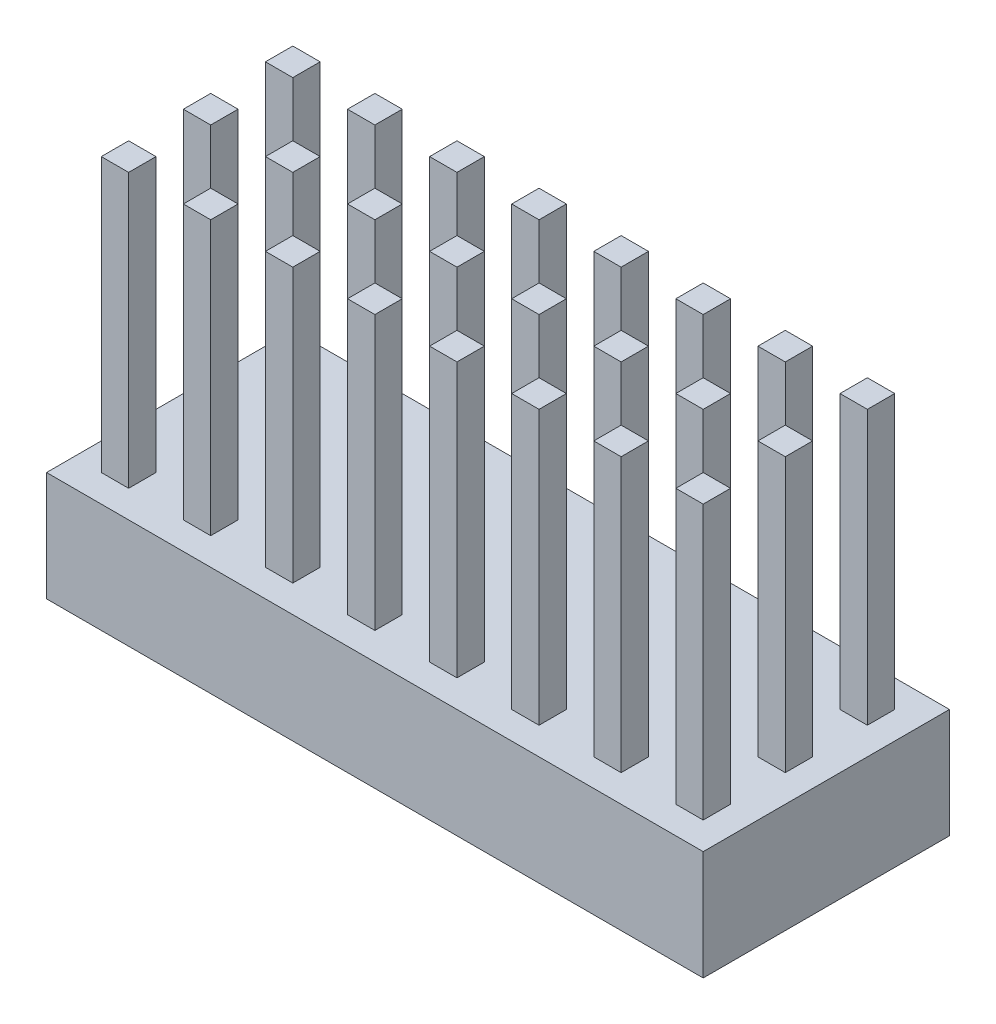
SolidWorks part; units mm, degrees
ref_plane "Front Plane" through (0, 0, 0) normal (0, 0, 1) x (1, 0, 0)
ref_plane "Top Plane" through (0, 0, 0) normal (0, 1, 0) x (1, 0, 0)
ref_plane "Right Plane" through (0, 0, 0) normal (1, 0, 0) x (0, 0, -1)
sketch "Sketch1" plane through (0, 0, 0) normal (0, 1, 0) x (1, 0, 0)
  line L1 (0, 0) -> (18.288, 0)
  line L2 (0, 0) -> (0, 6.858)
  line L3 (0, 6.858) -> (18.288, 6.858)
  line L4 (18.288, 0) -> (18.288, 6.858)
  dimension "D1" = 18.288
  dimension "D2" = 6.858
extrude "Extrude1" add sketch "Sketch1" along normal blind 3.048
sketch "Sketch2" plane through (0, 3.048, 0) normal (0, 1, 0) x (1, 0, 0)
  line L0 (0, 6.858) -> (0, 0) construction
  line L1 (3.048, 5.334) -> (3.81, 5.334)
  line L2 (3.048, 5.334) -> (3.048, 6.096)
  line L3 (3.048, 6.096) -> (3.81, 6.096)
  line L4 (3.81, 5.334) -> (3.81, 6.096)
  line L5 (0.762, 5.334) -> (1.524, 5.334)
  line L6 (0.762, 5.334) -> (0.762, 6.096)
  line L7 (0.762, 6.096) -> (1.524, 6.096)
  line L8 (1.524, 5.334) -> (1.524, 6.096)
  line L10 (18.288, 6.858) -> (0, 6.858) construction
  line L11 (5.334, 5.334) -> (6.096, 5.334)
  line L12 (5.334, 5.334) -> (5.334, 6.096)
  line L13 (5.334, 6.096) -> (6.096, 6.096)
  line L14 (6.096, 5.334) -> (6.096, 6.096)
  line L15 (7.62, 5.334) -> (8.382, 5.334)
  line L16 (7.62, 5.334) -> (7.62, 6.096)
  line L17 (7.62, 6.096) -> (8.382, 6.096)
  line L18 (8.382, 5.334) -> (8.382, 6.096)
  line L19 (9.906, 5.334) -> (10.668, 5.334)
  line L20 (9.906, 5.334) -> (9.906, 6.096)
  line L21 (9.906, 6.096) -> (10.668, 6.096)
  line L22 (10.668, 5.334) -> (10.668, 6.096)
  line L23 (12.192, 5.334) -> (12.954, 5.334)
  line L24 (12.192, 5.334) -> (12.192, 6.096)
  line L25 (12.192, 6.096) -> (12.954, 6.096)
  line L26 (12.954, 5.334) -> (12.954, 6.096)
  line L27 (14.478, 5.334) -> (15.24, 5.334)
  line L28 (14.478, 5.334) -> (14.478, 6.096)
  line L29 (14.478, 6.096) -> (15.24, 6.096)
  line L30 (15.24, 5.334) -> (15.24, 6.096)
  line L31 (16.764, 5.334) -> (17.526, 5.334)
  line L32 (16.764, 5.334) -> (16.764, 6.096)
  line L33 (16.764, 6.096) -> (17.526, 6.096)
  line L34 (17.526, 5.334) -> (17.526, 6.096)
  line L35 (0.762, 3.048) -> (1.524, 3.048)
  line L36 (0.762, 3.048) -> (0.762, 3.81)
  line L37 (0.762, 3.81) -> (1.524, 3.81)
  line L38 (1.524, 3.048) -> (1.524, 3.81)
  line L39 (3.048, 3.048) -> (3.81, 3.048)
  line L40 (3.048, 3.048) -> (3.048, 3.81)
  line L41 (3.048, 3.81) -> (3.81, 3.81)
  line L42 (3.81, 3.048) -> (3.81, 3.81)
  line L43 (5.334, 3.048) -> (6.096, 3.048)
  line L44 (5.334, 3.048) -> (5.334, 3.81)
  line L45 (5.334, 3.81) -> (6.096, 3.81)
  line L46 (6.096, 3.048) -> (6.096, 3.81)
  line L47 (7.62, 3.048) -> (8.382, 3.048)
  line L48 (7.62, 3.048) -> (7.62, 3.81)
  line L49 (7.62, 3.81) -> (8.382, 3.81)
  line L50 (8.382, 3.048) -> (8.382, 3.81)
  line L51 (9.906, 3.048) -> (10.668, 3.048)
  line L52 (9.906, 3.048) -> (9.906, 3.81)
  line L53 (9.906, 3.81) -> (10.668, 3.81)
  line L54 (10.668, 3.048) -> (10.668, 3.81)
  line L55 (12.192, 3.048) -> (12.954, 3.048)
  line L56 (12.192, 3.048) -> (12.192, 3.81)
  line L57 (12.192, 3.81) -> (12.954, 3.81)
  line L58 (12.954, 3.048) -> (12.954, 3.81)
  line L59 (14.478, 3.048) -> (15.24, 3.048)
  line L60 (14.478, 3.048) -> (14.478, 3.81)
  line L61 (14.478, 3.81) -> (15.24, 3.81)
  line L62 (15.24, 3.048) -> (15.24, 3.81)
  line L63 (16.764, 3.048) -> (17.526, 3.048)
  line L64 (16.764, 3.048) -> (16.764, 3.81)
  line L65 (16.764, 3.81) -> (17.526, 3.81)
  line L66 (17.526, 3.048) -> (17.526, 3.81)
  line L67 (0.762, 0.762) -> (1.524, 0.762)
  line L68 (0.762, 0.762) -> (0.762, 1.524)
  line L69 (0.762, 1.524) -> (1.524, 1.524)
  line L70 (1.524, 0.762) -> (1.524, 1.524)
  line L71 (3.048, 0.762) -> (3.81, 0.762)
  line L72 (3.048, 0.762) -> (3.048, 1.524)
  line L73 (3.048, 1.524) -> (3.81, 1.524)
  line L74 (3.81, 0.762) -> (3.81, 1.524)
  line L75 (5.334, 0.762) -> (6.096, 0.762)
  line L76 (5.334, 0.762) -> (5.334, 1.524)
  line L77 (5.334, 1.524) -> (6.096, 1.524)
  line L78 (6.096, 0.762) -> (6.096, 1.524)
  line L79 (7.62, 0.762) -> (8.382, 0.762)
  line L80 (7.62, 0.762) -> (7.62, 1.524)
  line L81 (7.62, 1.524) -> (8.382, 1.524)
  line L82 (8.382, 0.762) -> (8.382, 1.524)
  line L83 (9.906, 0.762) -> (10.668, 0.762)
  line L84 (9.906, 0.762) -> (9.906, 1.524)
  line L85 (9.906, 1.524) -> (10.668, 1.524)
  line L86 (10.668, 0.762) -> (10.668, 1.524)
  line L87 (12.192, 0.762) -> (12.954, 0.762)
  line L88 (12.192, 0.762) -> (12.192, 1.524)
  line L89 (12.192, 1.524) -> (12.954, 1.524)
  line L90 (12.954, 0.762) -> (12.954, 1.524)
  line L91 (14.478, 0.762) -> (15.24, 0.762)
  line L92 (14.478, 0.762) -> (14.478, 1.524)
  line L93 (14.478, 1.524) -> (15.24, 1.524)
  line L94 (15.24, 0.762) -> (15.24, 1.524)
  line L95 (16.764, 0.762) -> (17.526, 0.762)
  line L96 (16.764, 0.762) -> (16.764, 1.524)
  line L97 (16.764, 1.524) -> (17.526, 1.524)
  line L98 (17.526, 0.762) -> (17.526, 1.524)
  dimension "D3" = 0.762
  dimension "D4" = 0.762
  dimension "D5" = 0.762
  dimension "D8" = 0.762
extrude "Extrude2" add sketch "Sketch2" along normal blind 7.62
